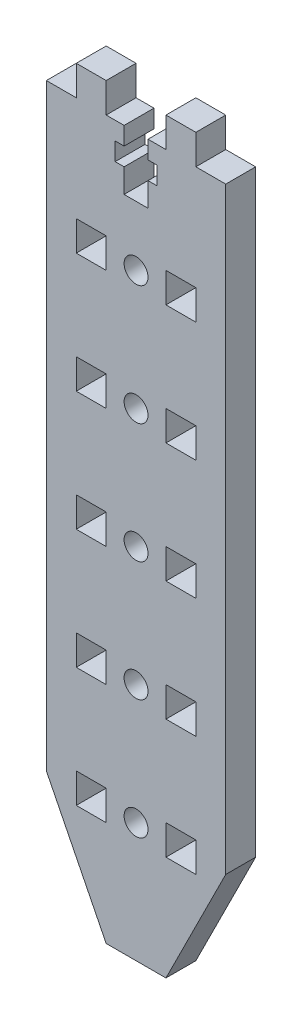
SolidWorks part; units mm, degrees
ref_plane "Plan de face" through (0, 0, 0) normal (0, 0, 1) x (1, 0, 0)
ref_plane "Plan de dessus" through (0, 0, 0) normal (0, 1, 0) x (1, 0, 0)
ref_plane "Plan de droite" through (0, 0, 0) normal (1, 0, 0) x (0, 0, -1)
sketch "Esquisse1" plane through (0, 0, 0) normal (0, 0, 1) x (1, 0, 0)
  line L0 (0, 0) -> (0, 100) construction
  line L1 (-10, 100) -> (-15, 100)
  line L2 (-15, 100) -> (-15, 0)
  line L3 (-15, 0) -> (-5, -20)
  line L4 (-5, -20) -> (5, -20)
  line L5 (15, 0) -> (5, -20)
  line L6 (15, 100) -> (15, 0)
  line L7 (10, 100) -> (15, 100)
  point P9 (0, -20)
  point P12 (10, 90)
  point P13 (7.2167, -35.3562)
  point P14 (0, 0)
  point P15 (10, 42.5)
  line B0 (3.5, 97) -> (3.5, 94)
  line B1 (-2, 94) -> (-2, 90)
  line B2 (2, 90) -> (2, 94)
  line B3 (3.5, 94) -> (2, 94)
  line B4 (0, 100) -> (0, 88.7792) construction
  line B5 (2, 100) -> (5, 100)
  line B6 (5, 105) -> (10, 105)
  line B7 (10, 105) -> (10, 100)
  line B8 (5, 105) -> (5, 100)
  line B9 (-2, 100) -> (-5, 100)
  line B10 (-5, 100) -> (-5, 105)
  line B11 (-5, 105) -> (-10, 105)
  line B12 (-10, 105) -> (-10, 100)
  line B13 (2, 100) -> (-2, 100) construction
  line B14 (-2, 100) -> (-2, 97)
  line B15 (-2, 94) -> (-3.5, 94)
  line B16 (-3.5, 97) -> (-2, 97)
  line B17 (-2, 90) -> (2, 90)
  line B18 (2, 97) -> (3.5, 97)
  line B19 (-3.5, 94) -> (-3.5, 97)
  line B20 (2, 97) -> (2, 100)
  line B21 (0, 90) -> (0, 100) construction
  line B22 (-5, 40) -> (5, 40) construction
  line B23 (-5, 42.5) -> (-10, 42.5)
  line B24 (-5, 42.5) -> (-5, 37.5)
  line B25 (-5, 37.5) -> (-10, 37.5)
  line B26 (-10, 42.5) -> (-10, 37.5)
  line B27 (5, 42.5) -> (10, 42.5)
  line B28 (5, 42.5) -> (5, 37.5)
  line B29 (5, 37.5) -> (10, 37.5)
  line B30 (10, 42.5) -> (10, 37.5)
  line B31 (0, 40) -> (0, 46.9724) construction
  circle B32 centre (0, 40) radius 2
  line B33 (-5, 20) -> (5, 20) construction
  line B34 (-5, 22.5) -> (-10, 22.5)
  line B35 (-5, 22.5) -> (-5, 17.5)
  line B36 (-5, 17.5) -> (-10, 17.5)
  line B37 (-10, 22.5) -> (-10, 17.5)
  line B38 (5, 22.5) -> (10, 22.5)
  line B39 (5, 22.5) -> (5, 17.5)
  line B40 (5, 17.5) -> (10, 17.5)
  line B41 (10, 22.5) -> (10, 17.5)
  line B42 (0, 20) -> (0, 26.9724) construction
  circle B43 centre (0, 20) radius 2
  line B44 (-5, 0) -> (5, 0) construction
  line B45 (-5, 2.5) -> (-10, 2.5)
  line B46 (-5, 2.5) -> (-5, -2.5)
  line B47 (-5, -2.5) -> (-10, -2.5)
  line B48 (-10, 2.5) -> (-10, -2.5)
  line B49 (5, 2.5) -> (10, 2.5)
  line B50 (5, 2.5) -> (5, -2.5)
  line B51 (5, -2.5) -> (10, -2.5)
  line B52 (10, 2.5) -> (10, -2.5)
  line B53 (0, 0) -> (0, 6.9724) construction
  circle B54 centre (0, 0) radius 2
  line B55 (-5, 60) -> (5, 60) construction
  line B56 (-5, 62.5) -> (-10, 62.5)
  line B57 (-5, 62.5) -> (-5, 57.5)
  line B58 (-5, 57.5) -> (-10, 57.5)
  line B59 (-10, 62.5) -> (-10, 57.5)
  line B60 (5, 62.5) -> (10, 62.5)
  line B61 (5, 62.5) -> (5, 57.5)
  line B62 (5, 57.5) -> (10, 57.5)
  line B63 (10, 62.5) -> (10, 57.5)
  line B64 (0, 60) -> (0, 66.9724) construction
  circle B65 centre (0, 60) radius 2
  line B66 (-5, 80) -> (5, 80) construction
  line B67 (-5, 82.5) -> (-10, 82.5)
  line B68 (-5, 82.5) -> (-5, 77.5)
  line B69 (-5, 77.5) -> (-10, 77.5)
  line B70 (-10, 82.5) -> (-10, 77.5)
  line B71 (5, 82.5) -> (10, 82.5)
  line B72 (5, 82.5) -> (5, 77.5)
  line B73 (5, 77.5) -> (10, 77.5)
  line B74 (10, 82.5) -> (10, 77.5)
  line B75 (0, 80) -> (0, 86.9724) construction
  circle B76 centre (0, 80) radius 2
  dimension "D1" = 5
  dimension "D2" = 20
  dimension "D3" = 20
  dimension "D4" = 60
  dimension "D5" = 20
  dimension "D6" = 10
  dimension "D7" = 20
  dimension "D8" = 20
sketch_block_instance "Insert M4 plots ep 5mm-1"
sketch_block "Insert M4 plots ep 5mm" parameters "D1"=10, "D2"=5, "D3"=5, "D4"=7, "D5"=4, "D6"=3, "D7"=3, "D8"=10
sketch_block_instance "Trou M4 plots 5mm-1"
sketch_block "Trou M4 plots 5mm" parameters "D2"=4, "D1"=5, "D3"=5, "D4"=10
sketch_block_instance "Trou M4 plots 5mm-4"
sketch_block_instance "Trou M4 plots 5mm-5"
sketch_block_instance "Trou M4 plots 5mm-6"
sketch_block_instance "Trou M4 plots 5mm-7"
extrude "Boss.-Extru.1" add sketch "Esquisse1" along normal blind 5
